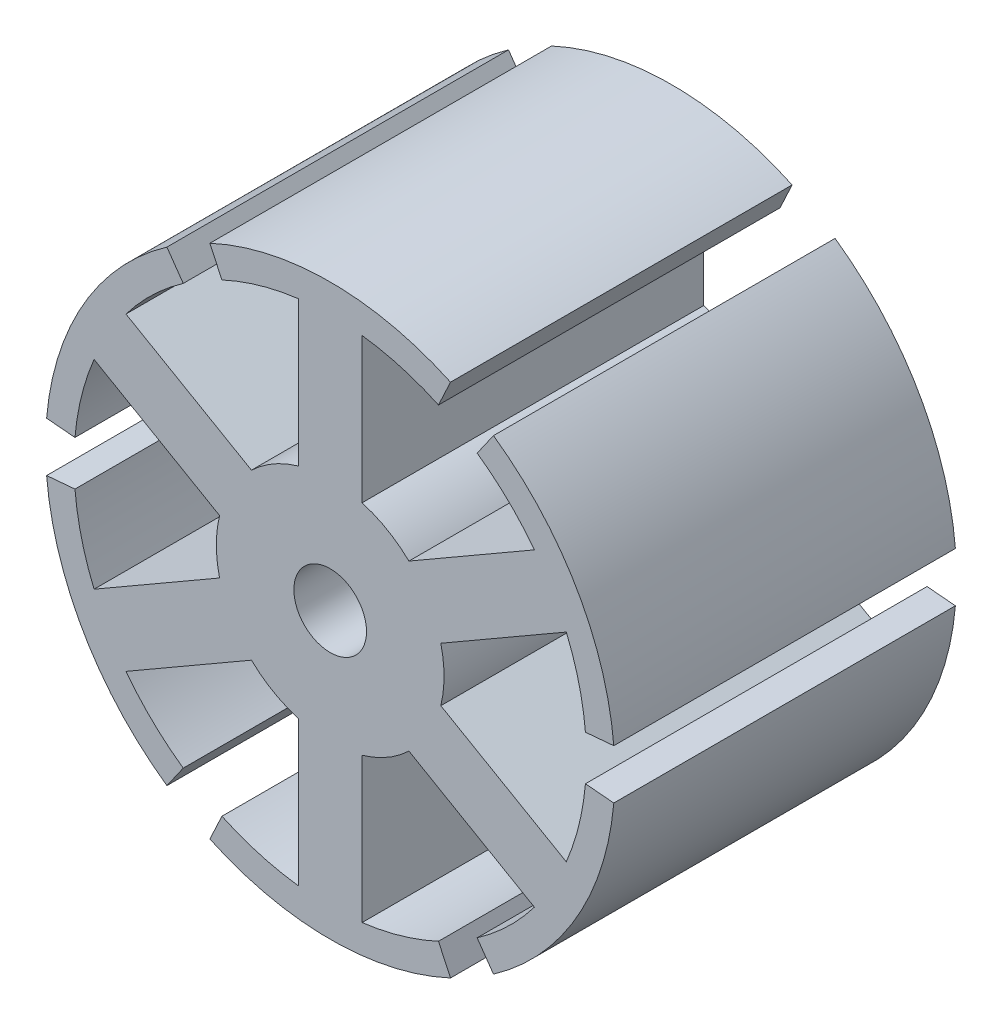
SolidWorks part; units mm, degrees
ref_plane "Front" through (0, 0, 0) normal (0, 0, 1) x (1, 0, 0)
ref_plane "Top" through (0, 0, 0) normal (0, 1, 0) x (1, 0, 0)
ref_plane "Right" through (0, 0, 0) normal (1, 0, 0) x (0, 0, -1)
sketch "Sketch1" plane through (0, 0, 0) normal (0, 0, 1) x (1, 0, 0)
  line L0 (0, 0) -> (25, 0) construction
  line L1 (0, 0) -> (12.5, 21.6506) construction
  line L2 (0, 0) -> (-12.5, 21.6506) construction
  line L3 (0, 0) -> (-25, 0) construction
  line L5 (0, 0) -> (-12.5, -21.6506) construction
  line L6 (0, 0) -> (12.5, -21.6506) construction
  line L7 (0, 0) -> (21.6506, 12.5) construction
  line L8 (5.6, 0) -> (20.7341, 8.7377) construction
  line L9 (2.8, 4.8497) -> (17.9341, 13.5874) construction
  line L10 (0, 0) -> (23.3491, 8.9342) construction
  line L14 (0, 0) -> (24.9049, 2.1789) construction
  line L16 (0, 0) -> (10.5655, 22.6577) construction
  line L17 (0, 0) -> (24.9049, -2.1789) construction
  line L18 (0, 0) -> (14.3394, 20.4788) construction
  circle A4 centre (0, 0) radius 25 construction
  circle A5 centre (0, 0) radius 22.5 construction
  circle A7 centre (0, 0) radius 10 construction
  dimension "D1" = 20
  dimension "D3" = 50
  dimension "D4" = 45
sketch "Sketch2" plane through (0, 0, 0) normal (0, 0, 1) x (1, 0, 0)
  circle A2 centre (0, 0) radius 25
  point P1 (0, 0)
extrude "Boss-Extrude2" add sketch "Sketch2" along normal blind 30
sketch "Sketch3" plane through (0, 0, 30) normal (0, 0, 1) x (1, 0, 0)
  line L0 (17.9341, 13.5874) -> (6.9138, 7.2249) construction
  line L1 (2.8, 4.8497) -> (17.9341, 13.5874) construction
  line L2 (20.7341, 8.7377) -> (9.7138, 2.3751) construction
  line L3 (5.6, 0) -> (20.7341, 8.7377) construction
  line L4 (24.9049, 2.1789) -> (22.4144, 1.961) construction
  line L5 (0, 0) -> (24.9049, 2.1789) construction
  line L6 (14.3394, 20.4788) -> (12.9055, 18.4309) construction
  line L7 (0, 0) -> (14.3394, 20.4788) construction
  line L8 (6.9138, -7.2249) -> (17.9341, -13.5874)
  line L9 (2.8, -9.6) -> (2.8, -22.3251)
  line L30 (20.7341, -8.7377) -> (9.7138, -2.3751) construction
  line L31 (17.9341, -13.5874) -> (6.9138, -7.2249) construction
  line L32 (14.3394, -20.4788) -> (12.9055, -18.4309) construction
  line L33 (24.9049, -2.1789) -> (22.4144, -1.961) construction
  line L34 (2.8, -22.3251) -> (2.8, -9.6) construction
  line L35 (-2.8, -22.3251) -> (-2.8, -9.6) construction
  line L36 (-10.5655, -22.6577) -> (-9.5089, -20.3919) construction
  line L37 (10.5655, -22.6577) -> (9.5089, -20.3919) construction
  line L38 (-17.9341, -13.5874) -> (-6.9138, -7.2249) construction
  line L39 (-20.7341, -8.7377) -> (-9.7138, -2.3751) construction
  line L40 (-24.9049, -2.1789) -> (-22.4144, -1.961) construction
  line L41 (-14.3394, -20.4788) -> (-12.9055, -18.4309) construction
  line L42 (-20.7341, 8.7377) -> (-9.7138, 2.3751) construction
  line L43 (-17.9341, 13.5874) -> (-6.9138, 7.2249) construction
  line L44 (-14.3394, 20.4788) -> (-12.9055, 18.4309) construction
  line L45 (-24.9049, 2.1789) -> (-22.4144, 1.961) construction
  line L46 (-2.8, 22.3251) -> (-2.8, 9.6) construction
  line L47 (2.8, 22.3251) -> (2.8, 9.6) construction
  line L48 (10.5655, 22.6577) -> (9.5089, 20.3919) construction
  line L49 (-10.5655, 22.6577) -> (-9.5089, 20.3919) construction
  line L50 (9.7138, -2.3751) -> (20.7341, -8.7377)
  line L51 (9.7138, 2.3751) -> (20.7341, 8.7377)
  line L52 (22.4144, 1.961) -> (24.9049, 2.1789)
  line L53 (22.4144, -1.961) -> (24.9049, -2.1789)
  line L54 (12.9055, -18.4309) -> (14.3394, -20.4788)
  line L55 (9.5089, -20.3919) -> (10.5655, -22.6577)
  line L56 (-2.8, -9.6) -> (-2.8, -22.3251)
  line L57 (-6.9138, -7.2249) -> (-17.9341, -13.5874)
  line L58 (-9.5089, -20.3919) -> (-10.5655, -22.6577)
  line L59 (-12.9055, -18.4309) -> (-14.3394, -20.4788)
  line L60 (-9.7138, -2.3751) -> (-20.7341, -8.7377)
  line L61 (-9.7138, 2.3751) -> (-20.7341, 8.7377)
  line L62 (-22.4144, -1.961) -> (-24.9049, -2.1789)
  line L63 (-22.4144, 1.961) -> (-24.9049, 2.1789)
  line L64 (-6.9138, 7.2249) -> (-17.9341, 13.5874)
  line L65 (-2.8, 9.6) -> (-2.8, 22.3251)
  line L66 (-12.9055, 18.4309) -> (-14.3394, 20.4788)
  line L67 (-9.5089, 20.3919) -> (-10.5655, 22.6577)
  line L68 (2.8, 9.6) -> (2.8, 22.3251)
  line L69 (6.9138, 7.2249) -> (17.9341, 13.5874)
  line L70 (9.5089, 20.3919) -> (10.5655, 22.6577)
  line L71 (12.9055, 18.4309) -> (14.3394, 20.4788)
  circle A0 centre (0, 0) radius 10 construction
  circle A1 centre (0, 0) radius 22.5 construction
  arc A2 (14.3394, 20.4788) -> (24.9049, 2.1789) centre (0, 0) cw construction
  arc A3 (12.9055, 18.4309) -> (17.9341, 13.5874) centre (0, 0) cw construction
  arc A4 (20.7341, 8.7377) -> (22.4144, 1.961) centre (0, 0) cw construction
  arc A26 (24.9049, -2.1789) -> (14.3394, -20.4788) centre (0, 0) cw construction
  arc A27 (22.4144, -1.961) -> (20.7341, -8.7377) centre (0, 0) cw construction
  arc A28 (17.9341, -13.5874) -> (12.9055, -18.4309) centre (0, 0) cw construction
  arc A29 (10.5655, -22.6577) -> (-10.5655, -22.6577) centre (0, 0) cw construction
  arc A30 (9.5089, -20.3919) -> (2.8, -22.3251) centre (0, 0) cw construction
  arc A31 (-2.8, -22.3251) -> (-9.5089, -20.3919) centre (0, 0) cw construction
  arc A32 (-14.3394, -20.4788) -> (-24.9049, -2.1789) centre (0, 0) cw construction
  arc A33 (-12.9055, -18.4309) -> (-17.9341, -13.5874) centre (0, 0) cw construction
  arc A34 (-20.7341, -8.7377) -> (-22.4144, -1.961) centre (0, 0) cw construction
  arc A35 (-24.9049, 2.1789) -> (-14.3394, 20.4788) centre (0, 0) cw construction
  arc A36 (-22.4144, 1.961) -> (-20.7341, 8.7377) centre (0, 0) cw construction
  arc A37 (-17.9341, 13.5874) -> (-12.9055, 18.4309) centre (0, 0) cw construction
  arc A38 (-10.5655, 22.6577) -> (10.5655, 22.6577) centre (0, 0) cw construction
  arc A39 (-9.5089, 20.3919) -> (-2.8, 22.3251) centre (0, 0) cw construction
  arc A40 (2.8, 22.3251) -> (9.5089, 20.3919) centre (0, 0) cw construction
  arc A42 (9.7138, 2.3751) -> (9.7138, -2.3751) centre (0, 0) cw
  arc A43 (20.7341, 8.7377) -> (22.4144, 1.961) centre (0, 0) cw
  arc A44 (20.7341, -8.7377) -> (22.4144, -1.961) centre (0, 0) ccw
  arc A45 (24.9049, -2.1789) -> (24.9049, 2.1789) centre (0, 0) ccw
  arc A46 (6.9138, -7.2249) -> (2.8, -9.6) centre (0, 0) cw
  arc A47 (2.8, -22.3251) -> (9.5089, -20.3919) centre (0, 0) ccw
  arc A48 (17.9341, -13.5874) -> (12.9055, -18.4309) centre (0, 0) cw
  arc A49 (10.5655, -22.6577) -> (14.3394, -20.4788) centre (0, 0) ccw
  arc A50 (-2.8, -9.6) -> (-6.9138, -7.2249) centre (0, 0) cw
  arc A51 (-17.9341, -13.5874) -> (-12.9055, -18.4309) centre (0, 0) ccw
  arc A52 (-2.8, -22.3251) -> (-9.5089, -20.3919) centre (0, 0) cw
  arc A53 (-14.3394, -20.4788) -> (-10.5655, -22.6577) centre (0, 0) ccw
  arc A54 (-9.7138, -2.3751) -> (-9.7138, 2.3751) centre (0, 0) cw
  arc A55 (-20.7341, 8.7377) -> (-22.4144, 1.961) centre (0, 0) ccw
  arc A56 (-20.7341, -8.7377) -> (-22.4144, -1.961) centre (0, 0) cw
  arc A57 (-24.9049, 2.1789) -> (-24.9049, -2.1789) centre (0, 0) ccw
  arc A58 (-6.9138, 7.2249) -> (-2.8, 9.6) centre (0, 0) cw
  arc A59 (-2.8, 22.3251) -> (-9.5089, 20.3919) centre (0, 0) ccw
  arc A60 (-17.9341, 13.5874) -> (-12.9055, 18.4309) centre (0, 0) cw
  arc A61 (-10.5655, 22.6577) -> (-14.3394, 20.4788) centre (0, 0) ccw
  arc A62 (2.8, 9.6) -> (6.9138, 7.2249) centre (0, 0) cw
  arc A63 (17.9341, 13.5874) -> (12.9055, 18.4309) centre (0, 0) ccw
  arc A64 (2.8, 22.3251) -> (9.5089, 20.3919) centre (0, 0) cw
  arc A65 (14.3394, 20.4788) -> (10.5655, 22.6577) centre (0, 0) ccw
  point P68 (0, 0)
  point P129 (0, 0)
extrude "Cut-Extrude2" cut sketch "Sketch3" against normal blind 30
sketch "Sketch4" plane through (0, 0, 30) normal (0, 0, 1) x (1, 0, 0)
  circle A0 centre (0, 0) radius 3.19
  dimension "D1" = 6.38
extrude "Cut-Extrude3" cut sketch "Sketch4" against normal blind 30
